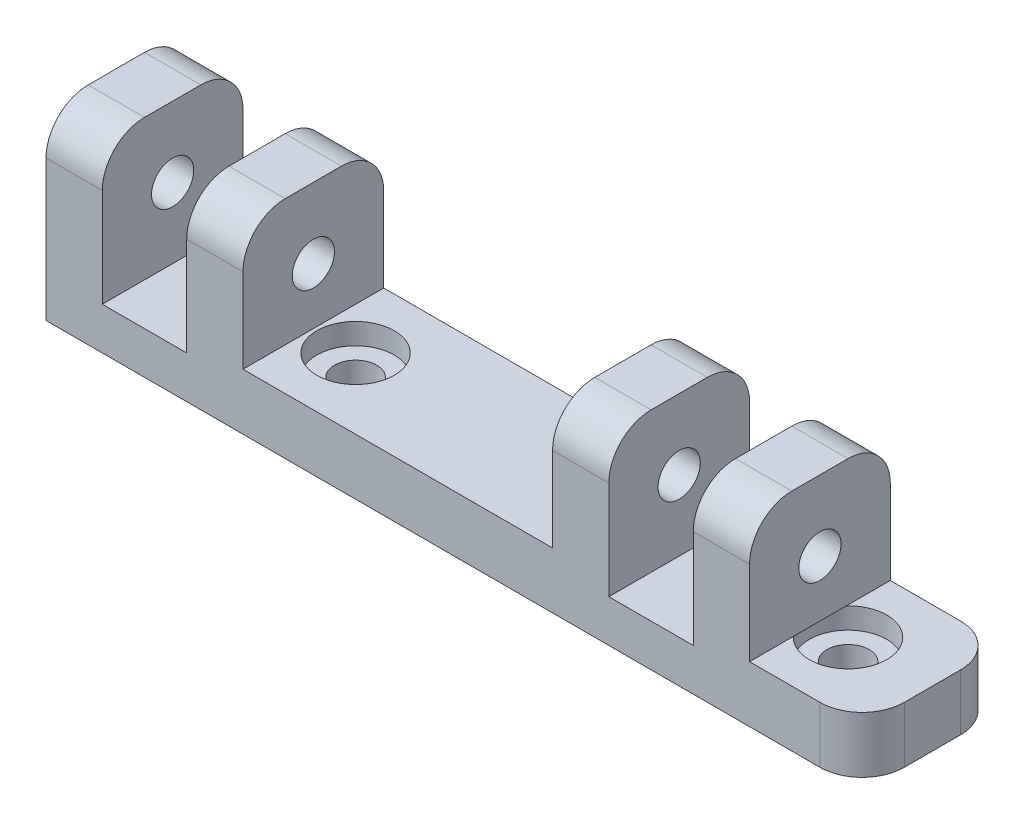
SolidWorks part; units mm, degrees
ref_plane "前视基准面" through (0, 0, 0) normal (0, 0, 1) x (1, 0, 0)
ref_plane "上视基准面" through (0, 0, 0) normal (0, 1, 0) x (1, 0, 0)
ref_plane "右视基准面" through (0, 0, 0) normal (1, 0, 0) x (0, 0, -1)
sketch "草图1" plane through (0, 0, 0) normal (0, 0, 1) x (1, 0, 0)
  line L0 (0, 0) -> (0, 13)
  line L1 (0, 13) -> (4, 13)
  line L2 (4, 13) -> (4, 3)
  line L3 (4, 3) -> (10, 3)
  line L4 (10, 3) -> (10, 13)
  line L5 (10, 13) -> (14, 13)
  line L6 (14, 13) -> (14, 4)
  line L7 (14, 4) -> (36, 4)
  line L8 (36, 4) -> (36, 13)
  line L9 (36, 13) -> (40, 13)
  line L10 (40, 13) -> (40, 3)
  line L11 (40, 3) -> (46, 3)
  line L12 (46, 3) -> (46, 13)
  line L13 (46, 13) -> (50, 13)
  line L14 (50, 13) -> (50, 0)
  line L15 (50, 0) -> (0, 0)
  dimension "D1" = 6
  dimension "D2" = 6
  dimension "D3" = 4
  dimension "D4" = 4
  dimension "D5" = 4
  dimension "D6" = 4
  dimension "D7" = 50
  dimension "D8" = 4
  dimension "D9" = 3
  dimension "D10" = 3
  dimension "D11" = 10
  dimension "D12" = 10
  dimension "D13" = 10
  dimension "D14" = 10
extrude "凸台-拉伸1" add sketch "草图1" along normal blind 10
sketch "草图2" plane through (50, 0, 0) normal (1, 0, 0) x (0, 0, -1)
  line L0 (0, 0) -> (0, 13) construction
  line L1 (-10, 0) -> (0, 0)
  line L2 (-10, 0) -> (-10, 4)
  line L3 (-10, 4) -> (0, 4)
  line L4 (0, 0) -> (0, 4)
  dimension "D1" = 4
extrude "凸台-拉伸2" add sketch "草图2" along normal blind 8
sketch "草图3" plane through (0, 4, 0) normal (0, 1, 0) x (1, 0, 0)
  line L0 (14, -10) -> (14, 0) construction
  line L1 (36, 0) -> (14, 0) construction
  circle A0 centre (17, -5) radius 1.5
  circle A1 centre (52, -5) radius 1.5
  dimension "D1" = 3
  dimension "D2" = 35
  dimension "D3" = 5
extrude "切除-拉伸1" cut sketch "草图3" against normal blind 5
sketch "草图4" plane through (0, 4, 0) normal (0, 1, 0) x (1, 0, 0)
  circle A0 centre (17, -5) radius 2.75
  circle A1 centre (52, -5) radius 2.75
  dimension "D1" = 5.5
extrude "切除-拉伸2" cut sketch "草图4" against normal blind 1.5
fillet "圆角1" radius 3 8 edges at (2, 13, 0) (2, 13, 10) (12, 13, 10) (12, 13, 0) (38, 13, 0) (48, 13, 0) (38, 13, 10) (48, 13, 10)
sketch "草图5" plane through (50, 0, 0) normal (1, 0, 0) x (0, 0, -1)
  line L0 (-7, 13) -> (-3, 13) construction
  circle A0 centre (-5, 8) radius 1.5
  dimension "D1" = 5
extrude "切除-拉伸3" cut sketch "草图5" against normal through all
fillet "圆角2" radius 3 2 edges at (58, 2, 0) (58, 2, 10)
